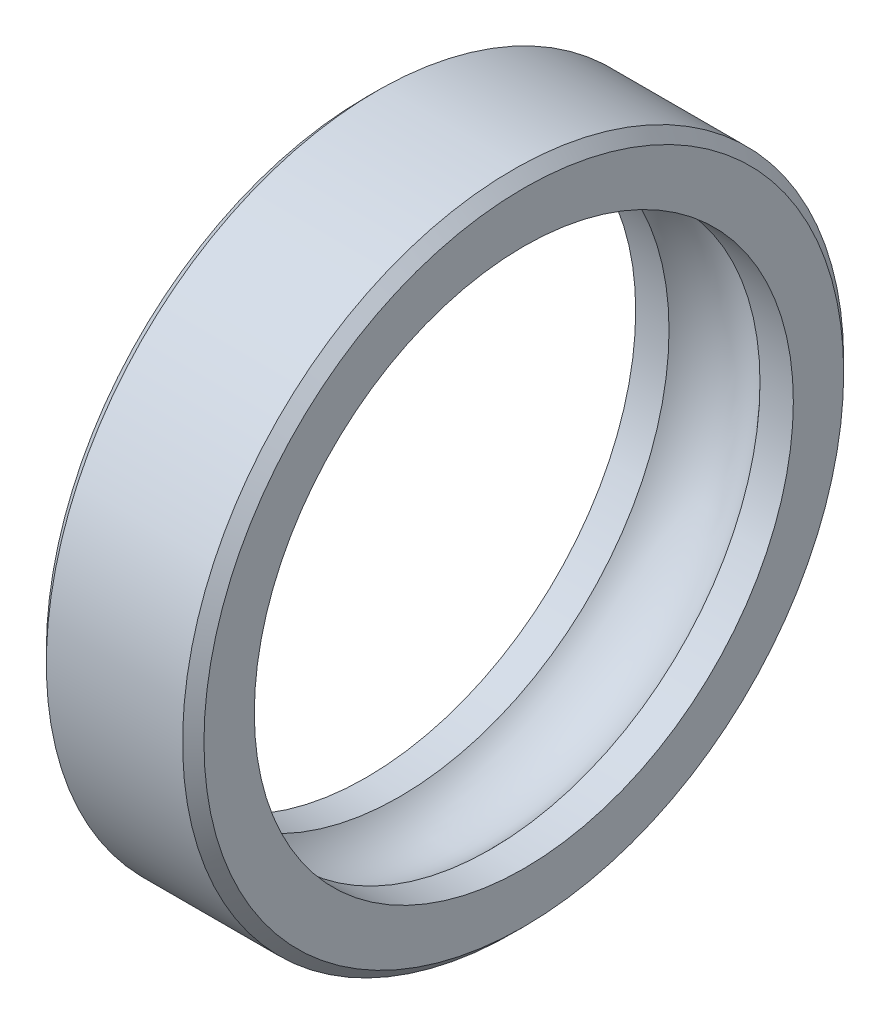
SolidWorks part; units mm, degrees
ref_plane "Front Plane" through (0, 0, 0) normal (0, 0, 1) x (1, 0, 0)
ref_plane "Top Plane" through (0, 0, 0) normal (0, 1, 0) x (1, 0, 0)
ref_plane "Right Plane" through (0, 0, 0) normal (1, 0, 0) x (0, 0, -1)
sketch "Sketch2" plane through (0, 0, 0) normal (0, 0, 1) x (1, 0, 0)
  line L0 (-21.5841, 0) -> (20.5701, 0)
  line L1 (0, 59) -> (0, 57)
  line L2 (-15.5, 65) -> (15.5, 65)
  line L3 (-15.5, 65) -> (-15.5, 53)
  line L4 (-15.5, 53) -> (-8.9443, 53)
  line L5 (15.5, 65) -> (15.5, 53)
  line L6 (-15.5, 65) -> (15.5, 53) construction
  line L7 (-15.5, 53) -> (15.5, 65) construction
  line L8 (8.9443, 53) -> (15.5, 53)
  arc A0 (8.9443, 53) -> (-8.9443, 53) centre (0, 45) ccw
  point P3 (0, 59)
  dimension "D5" = 12
  dimension "D6" = 20.5701
  dimension "D1" = 31
  dimension "D2" = 53
  dimension "D3" = 65
  dimension "D4" = 8
  dimension "D7" = 21.5841
revolve "Revolve1" add sketch "Sketch2" angle 360 about L0
chamfer "Chamfer1" distance 2.1 angle 45 2 edges at (-15.5, 0, 65) (15.5, 0, 65)
